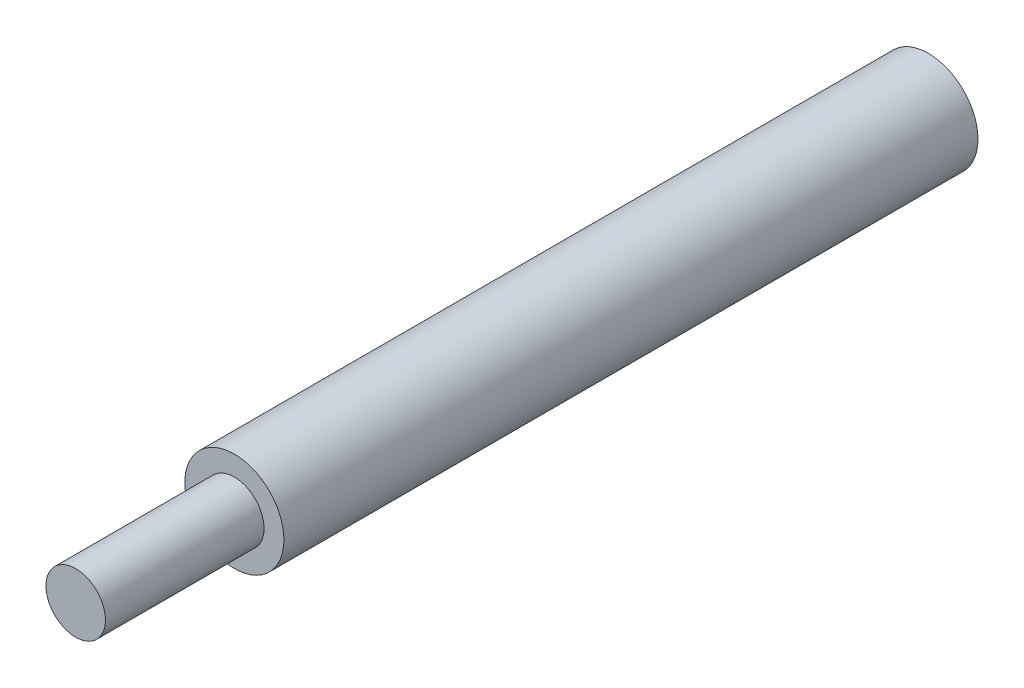
SolidWorks part; units mm, degrees
ref_plane "Front Plane" through (0, 0, 0) normal (0, 0, 1) x (1, 0, 0)
ref_plane "Top Plane" through (0, 0, 0) normal (0, 1, 0) x (1, 0, 0)
ref_plane "Right Plane" through (0, 0, 0) normal (1, 0, 0) x (0, 0, -1)
sketch "Sketch1" plane through (0, 0, 0) normal (0, 0, 1) x (1, 0, 0)
  circle A0 centre (0, 0) radius 2.5
  dimension "D1" = 5
extrude "Boss-Extrude1" add sketch "Sketch1" along normal blind 35
sketch "Sketch2" plane through (0, 0, 35) normal (0, 0, 1) x (1, 0, 0)
  circle A0 centre (0, 0) radius 1.5
  dimension "D1" = 3
extrude "Boss-Extrude2" add sketch "Sketch2" along normal blind 8
